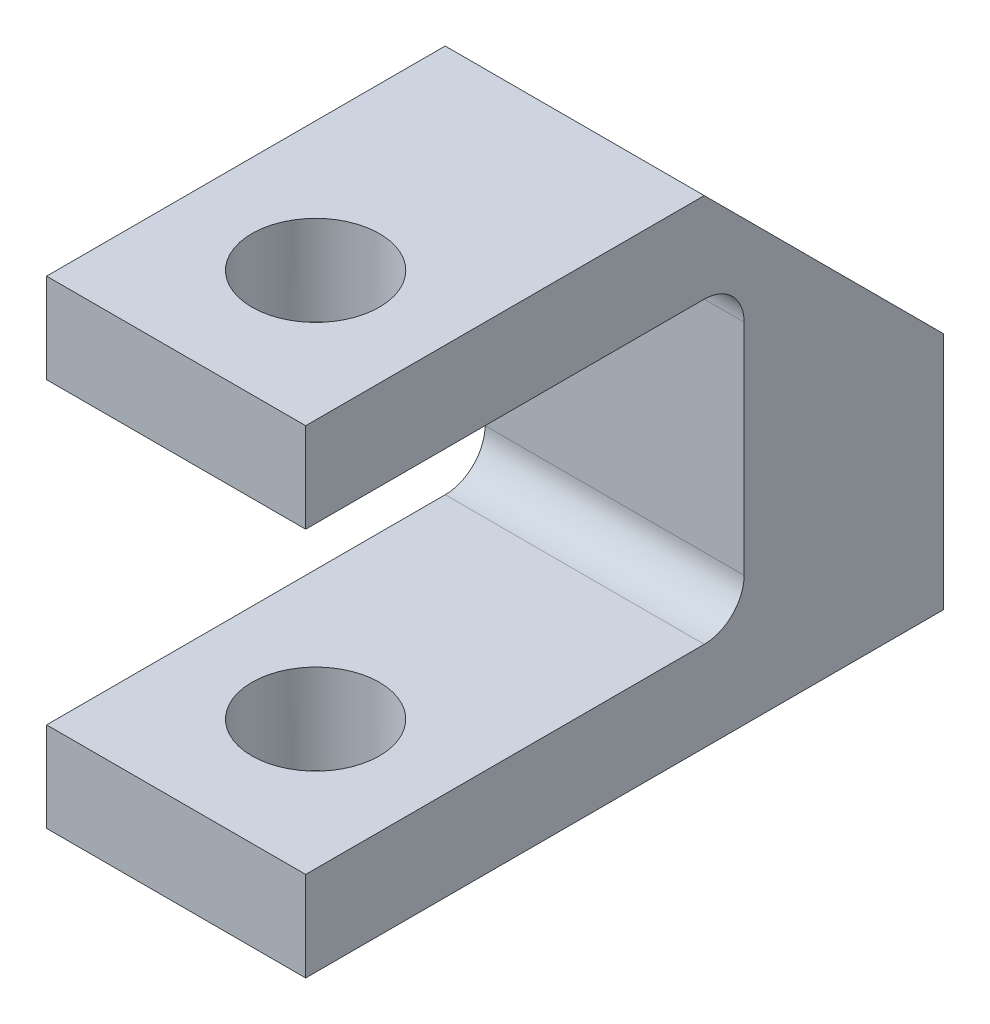
SolidWorks part; units mm, degrees
ref_plane "Front Plane" through (0, 0, 0) normal (0, 0, 1) x (1, 0, 0)
ref_plane "Top Plane" through (0, 0, 0) normal (0, 1, 0) x (1, 0, 0)
ref_plane "Right Plane" through (0, 0, 0) normal (1, 0, 0) x (0, 0, -1)
sketch "Sketch1" plane through (0, 0, 0) normal (1, 0, 0) x (0, 0, -1)
  line L1 (-8, -6) -> (8, -6)
  line L2 (-8, -6) -> (-8, 6)
  line L3 (-8, 6) -> (8, 6)
  line L4 (8, -6) -> (8, 6)
  line L5 (-8, -6) -> (8, 6) construction
  line L6 (-8, 6) -> (8, -6) construction
  point P0 (0, 0)
  dimension "D1" = 16
  dimension "D2" = 12
extrude "Boss-Extrude1" add sketch "Sketch1" against normal blind 6.5
sketch "Sketch2" plane through (0, 0, 0) normal (1, 0, 0) x (0, 0, -1)
  line L0 (8, 0) -> (2, 6)
  line L1 (8, -6) -> (8, 6) construction
  line L2 (8, 6) -> (-8, 6) construction
  line L3 (2, 6) -> (8, 6)
  line L4 (8, 6) -> (8, 0)
  dimension "D1" = 6
  dimension "D2" = 6
extrude "Cut-Extrude1" cut sketch "Sketch2" against normal through all
sketch "Sketch3" plane through (0, 0, 8) normal (0, 0, 1) x (1, 0, 0)
  line L0 (-3.25, 6) -> (-3.25, -6) construction
  line L1 (-6.5, 6) -> (0, 6) construction
  line L2 (-6.5, -6) -> (0, -6) construction
  line L4 (-10.25, -3.75) -> (3.75, -3.75)
  line L5 (-10.25, -3.75) -> (-10.25, 3.75)
  line L6 (-10.25, 3.75) -> (3.75, 3.75)
  line L7 (3.75, -3.75) -> (3.75, 3.75)
  line L8 (-10.25, -3.75) -> (3.75, 3.75) construction
  line L9 (-10.25, 3.75) -> (3.75, -3.75) construction
  point P6 (-3.25, 0)
  dimension "D1" = 14
  dimension "D2" = 7.5
extrude "Cut-Extrude2" cut sketch "Sketch3" against normal blind 11 contours L5 L4 L7 L6
sketch "Sketch4" plane through (0, 6, 0) normal (0, 1, 0) x (1, 0, 0)
  line L0 (-3.25, 2) -> (-3.25, -8) construction
  line L1 (-6.5, 2) -> (0, 2) construction
  line L2 (-6.5, -8) -> (0, -8) construction
  circle A1 centre (-3.25, -4.5) radius 1.6
  dimension "D1" = 3.2
  dimension "D2" = 3.5
extrude "Cut-Extrude3" cut sketch "Sketch4" against normal through all
fillet "Fillet1" radius 1 2 edges at (-3.25, -3.75, -3) (-3.25, 3.75, -3)
